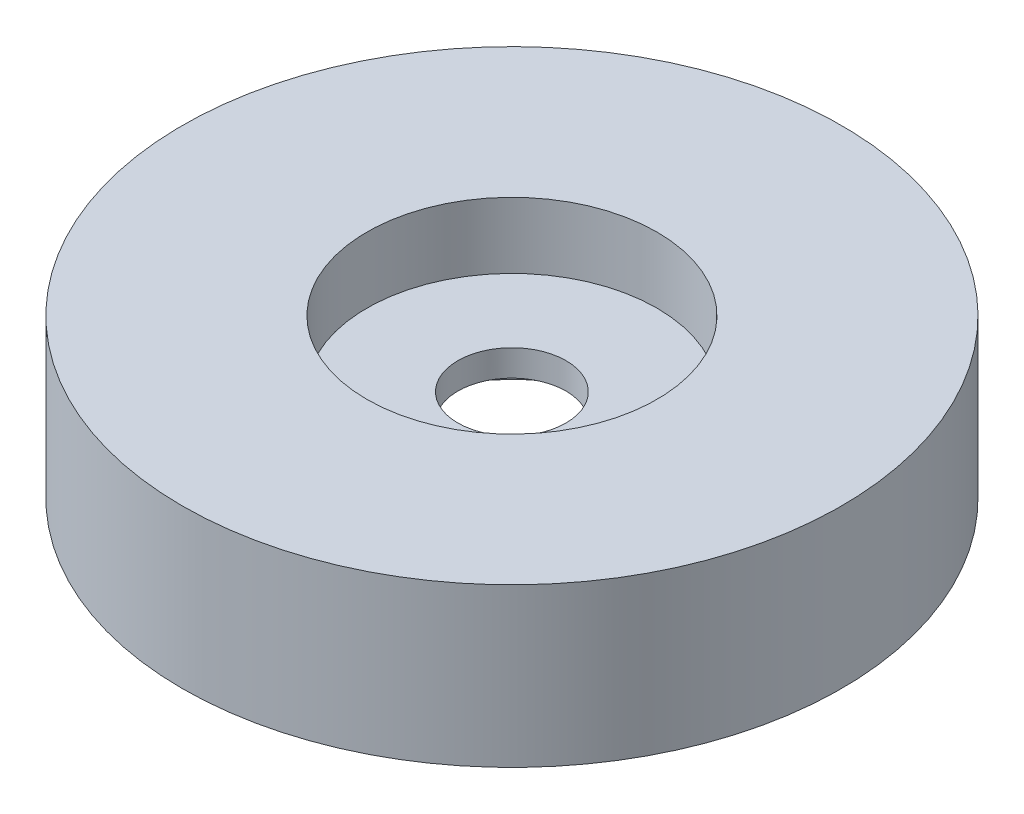
SolidWorks part; units mm, degrees
ref_plane "Front Plane" through (0, 0, 0) normal (0, 0, 1) x (1, 0, 0)
ref_plane "Top Plane" through (0, 0, 0) normal (0, 1, 0) x (1, 0, 0)
ref_plane "Right Plane" through (0, 0, 0) normal (1, 0, 0) x (0, 0, -1)
sketch "Sketch1" plane through (0, 0, 0) normal (0, 1, 0) x (1, 0, 0)
  circle A0 centre (0, 0) radius 25
  circle A1 centre (0, 0) radius 4.1
extrude "Boss-Extrude1" add sketch "Sketch1" along normal blind 12
sketch "Sketch2" plane through (0, 12, 0) normal (0, 1, 0) x (1, 0, 0)
  circle A0 centre (0, 0) radius 11
extrude "Cut-Extrude1" cut sketch "Sketch2" against normal blind 5
sketch "Sketch3" plane through (0, 0, 0) normal (0, -1, 0) x (1, 0, 0)
  circle A0 centre (0, 0) radius 11.05
extrude "Cut-Extrude2" cut sketch "Sketch3" against normal blind 5
